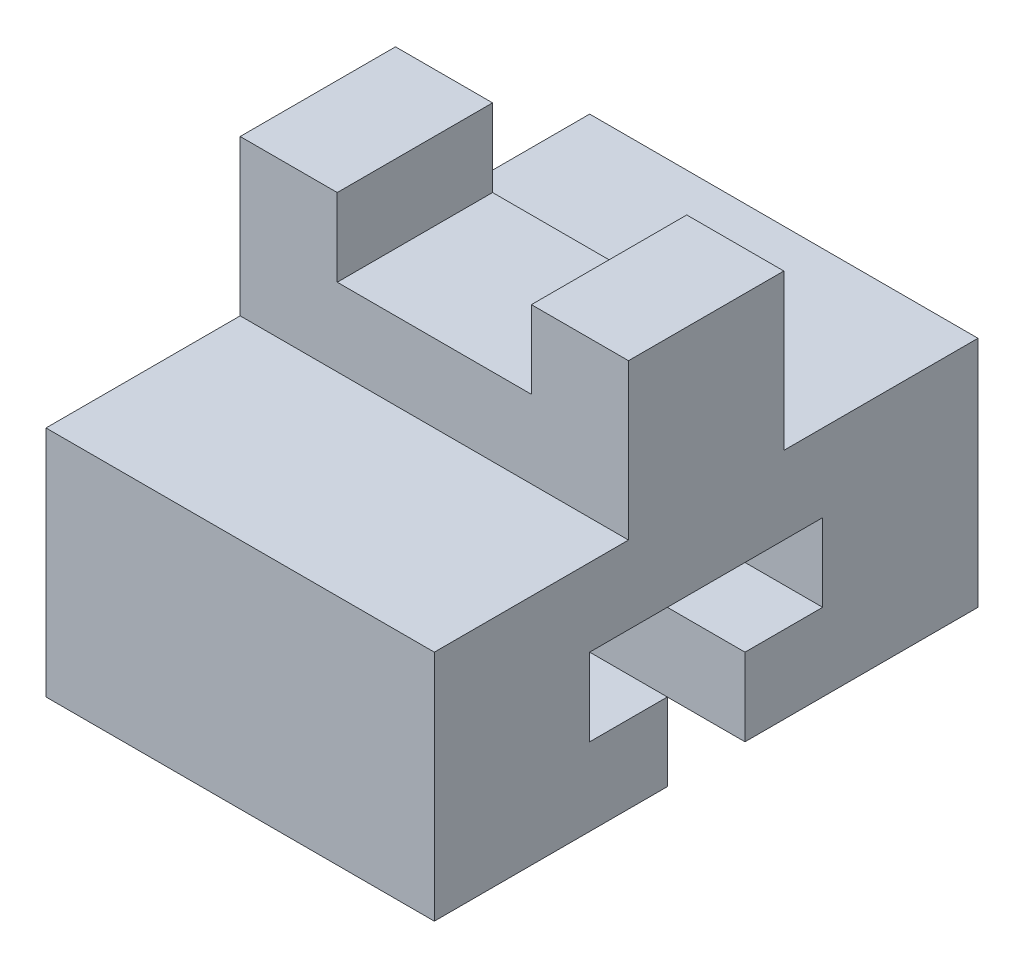
SolidWorks part; units mm, degrees
material "Alloy Steel"
ref_plane "Front Plane" through (0, 0, 0) normal (0, 0, 1) x (1, 0, 0)
ref_plane "Top Plane" through (0, 0, 0) normal (0, 1, 0) x (1, 0, 0)
ref_plane "Right Plane" through (0, 0, 0) normal (1, 0, 0) x (0, 0, -1)
sketch "Sketch1" plane through (0, 0, 0) normal (1, 0, 0) x (0, 0, -1)
  line L0 (0, 0) -> (30, 0)
  line L1 (30, 0) -> (30, 10)
  line L2 (30, 10) -> (20, 10)
  line L3 (20, 10) -> (20, 20)
  line L4 (20, 20) -> (50, 20)
  line L5 (50, 20) -> (50, 10)
  line L6 (50, 10) -> (40, 10)
  line L7 (40, 10) -> (40, 0)
  line L8 (40, 0) -> (70, 0)
  line L9 (70, 0) -> (70, 30)
  line L10 (70, 30) -> (45, 30)
  line L11 (45, 30) -> (45, 50)
  line L12 (45, 50) -> (25, 50)
  line L13 (25, 50) -> (25, 30)
  line L14 (25, 30) -> (0, 30)
  line L15 (0, 30) -> (0, 0)
  dimension "D1" = 70
  dimension "D2" = 10
  dimension "D3" = 10
  dimension "D4" = 10
  dimension "D5" = 30
  dimension "D6" = 30
  dimension "D7" = 50
  dimension "D8" = 20
extrude "Boss-Extrude1" add sketch "Sketch1" against normal blind 50
sketch "Sketch2" plane through (0, 0, -25) normal (0, 0, 1) x (1, 0, 0)
  line L0 (-50, 50) -> (0, 50) construction
  line L1 (-37.5, 50) -> (-12.5, 50)
  line L2 (-37.5, 50) -> (-37.5, 40)
  line L3 (-37.5, 40) -> (-12.5, 40)
  line L4 (-12.5, 50) -> (-12.5, 40)
  point P6 (-25, 50)
  point P7 (-25, 40)
  dimension "D1" = 10
  dimension "D2" = 25
extrude "Cut-Extrude1" cut sketch "Sketch2" against normal through all
